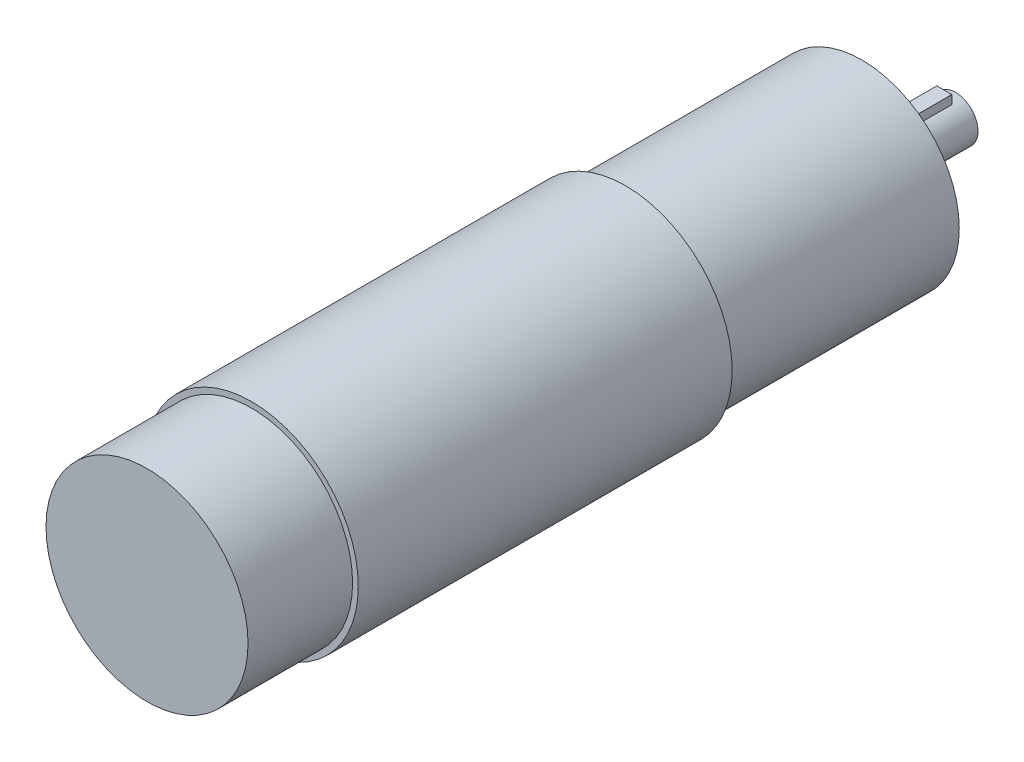
SolidWorks part; units mm, degrees
ref_plane "Front Plane" through (0, 0, 0) normal (0, 0, 1) x (1, 0, 0)
ref_plane "Top Plane" through (0, 0, 0) normal (0, 1, 0) x (1, 0, 0)
ref_plane "Right Plane" through (0, 0, 0) normal (1, 0, 0) x (0, 0, -1)
sketch "Sketch1" plane through (0, 0, 0) normal (1, 0, 0) x (0, 0, -1)
  line L0 (-10.8795, 0) -> (232.2227, 0) construction
  line L1 (0, 0) -> (207.0541, 0)
  line L2 (0, 0) -> (0, 26.9875)
  line L3 (0, 26.9875) -> (27.94, 26.9875)
  line L4 (27.94, 26.9875) -> (27.94, 28.5)
  line L5 (27.94, 28.5) -> (127.8372, 28.5)
  line L6 (127.8372, 28.5) -> (127.8372, 26)
  line L7 (127.8372, 26) -> (191.008, 26)
  line L8 (191.008, 26) -> (191.008, 16)
  line L9 (191.008, 16) -> (194.008, 16)
  line L10 (194.008, 16) -> (194.008, 6)
  line L11 (194.008, 6) -> (216.008, 6)
  line L12 (216.008, 6) -> (216.008, 2.159)
  line L13 (216.008, 2.159) -> (215.4365, 1.5875)
  line L14 (215.4365, 1.5875) -> (208.008, 1.5875)
  line L15 (208.008, 1.5875) -> (207.0541, 0)
  dimension "D1" = 57
  dimension "D2" = 32
  dimension "D3" = 52
  dimension "D4" = 3
  dimension "D5" = 12
  dimension "D6" = 25
  dimension "D7" = 163.068
  dimension "D8" = 27.94
  dimension "D9" = 59
  dimension "D10" = 45
  dimension "D11" = 3.175
  dimension "D12" = 4.318
  dimension "D13" = 8
revolve "Revolve1" add sketch "Sketch1" angle 360 about L0
sketch "Sketch2" plane through (0, 0, 0) normal (1, 0, 0) x (0, 0, -1)
  line L0 (216.008, 6) -> (194.008, 6) construction
  line L1 (197.008, 8) -> (213.008, 8)
  line L2 (197.008, 8) -> (197.008, 4.9187)
  line L3 (197.008, 4.9187) -> (213.008, 4.9187)
  line L4 (213.008, 8) -> (213.008, 4.9187)
  line L5 (216.008, -6) -> (216.008, 6) construction
  dimension "D1" = 2
  dimension "D2" = 16
  dimension "D3" = 3
extrude "Boss-Extrude1" add sketch "Sketch2" along normal mid plane 4
